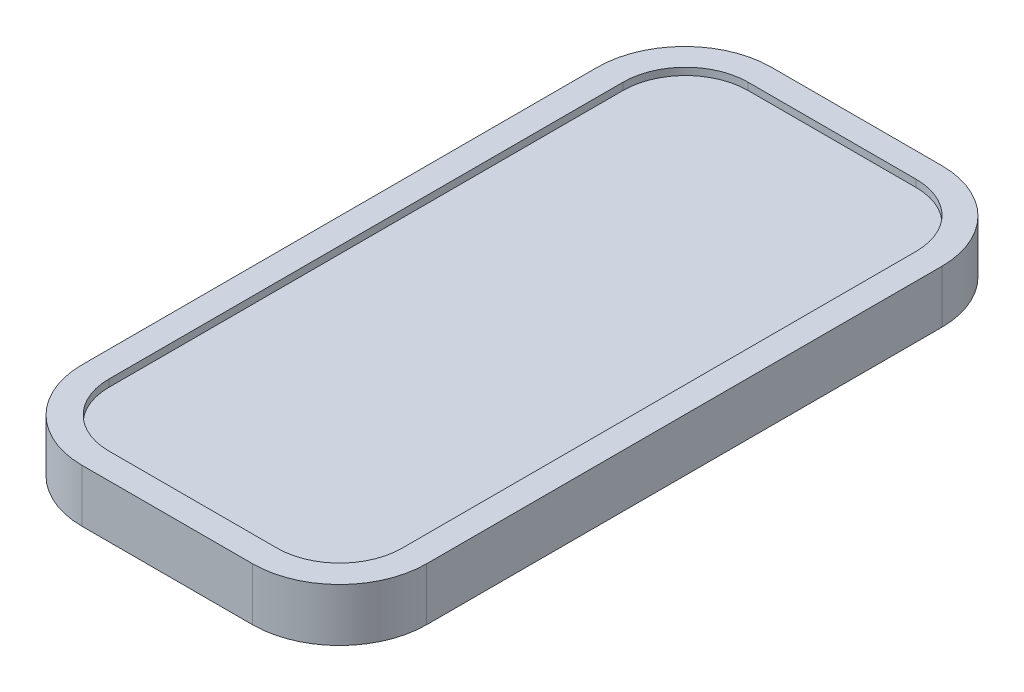
SolidWorks part; units mm, degrees
ref_plane "Front Plane" through (0, 0, 0) normal (0, 0, 1) x (1, 0, 0)
ref_plane "Top Plane" through (0, 0, 0) normal (0, 1, 0) x (1, 0, 0)
ref_plane "Right Plane" through (0, 0, 0) normal (1, 0, 0) x (0, 0, -1)
sketch "Sketch1" plane through (0, 0, 0) normal (0, 1, 0) x (1, 0, 0)
  line L1 (165.1, 0) -> (609.6, 0)
  line L2 (0, 165.1) -> (0, 1524)
  line L3 (165.1, 1689.1) -> (609.6, 1689.1)
  line L4 (774.7, 165.1) -> (774.7, 1524)
  arc A0 (0, 1524) -> (165.1, 1689.1) centre (165.1, 1524) cw
  arc A1 (774.7, 1524) -> (609.6, 1689.1) centre (609.6, 1524) ccw
  arc A2 (0, 165.1) -> (165.1, 0) centre (165.1, 165.1) ccw
  arc A3 (774.7, 165.1) -> (609.6, 0) centre (609.6, 165.1) cw
  point P7 (0, 1689.1)
  point P12 (0, 0)
  point P15 (774.7, 0)
  dimension "D3" = 165.1
  dimension "D4" = 165.1
  dimension "D5" = 165.1
  dimension "D6" = 165.1
  dimension "D1" = 774.7
  dimension "D2" = 1689.1
extrude "Boss-Extrude2" add sketch "Sketch1" against normal blind 10
sketch "Sketch2" plane through (0, 0, 0) normal (0, 1, 0) x (1, 0, 0)
  line L1 (165.1, 0) -> (609.6, 0)
  line L2 (0, 165.1) -> (0, 1524)
  line L3 (165.1, 1689.1) -> (609.6, 1689.1)
  line L4 (774.7, 165.1) -> (774.7, 1524)
  line L5 (162.1025, -68.0875) -> (612.5975, -68.0875)
  line L6 (-68.0875, 162.1025) -> (-68.0875, 1523.9975)
  line L7 (162.1025, 1754.1875) -> (612.5975, 1754.1875)
  line L8 (842.7875, 162.1025) -> (842.7875, 1523.9975)
  arc A0 (165.1, 1689.1) -> (0, 1524) centre (165.1, 1524) ccw
  arc A1 (609.6, 1689.1) -> (774.7, 1524) centre (609.6, 1524) cw
  arc A2 (774.7, 165.1) -> (609.6, 0) centre (609.6, 165.1) cw
  arc A3 (0, 165.1) -> (165.1, 0) centre (165.1, 165.1) ccw
  arc A4 (-68.0875, 162.1025) -> (162.1025, -68.0875) centre (162.1025, 162.1025) ccw
  arc A5 (842.7875, 162.1025) -> (612.5975, -68.0875) centre (612.5975, 162.1025) cw
  arc A6 (612.5975, 1754.1875) -> (842.7875, 1523.9975) centre (612.5975, 1523.9975) cw
  arc A7 (-68.0875, 1523.9975) -> (162.1025, 1754.1875) centre (162.1025, 1523.9975) cw
  point P14 (774.7, 1689.1)
  point P19 (0, 0)
  dimension "D5" = 165.1
  dimension "D6" = 165.1
  dimension "D7" = 165.1
  dimension "D8" = 165.1
  dimension "D9" = 230.19
  dimension "D10" = 230.19
  dimension "D11" = 230.19
  dimension "D12" = 230.19
  dimension "D1" = 65.0875
  dimension "D2" = 68.0875
  dimension "D3" = 68.0875
  dimension "D4" = 68.0875
extrude "Boss-Extrude3" add sketch "Sketch2" along normal blind 19.05 separate body
sketch "Sketch3" plane through (0, 0, 0) normal (0, -1, 0) x (1, 0, 0)
  line L0 (-68.0875, -1523.9975) -> (-68.0875, -162.1025) construction
  line L1 (162.1025, -1754.1875) -> (612.5975, -1754.1875)
  line L2 (-68.0875, -1523.9975) -> (-68.0875, -162.1025)
  line L3 (162.1025, 68.0875) -> (612.5975, 68.0875)
  line L4 (842.7875, -1523.9975) -> (842.7875, -162.1025)
  line L5 (612.5975, -1754.1875) -> (162.1025, -1754.1875) construction
  line L6 (842.7875, -162.1025) -> (842.7875, -1523.9975) construction
  line L7 (162.1025, 68.0875) -> (612.5975, 68.0875) construction
  line L8 (162.1025, -1734.1875) -> (612.5975, -1734.1875)
  line L9 (822.7875, -1523.9975) -> (822.7875, -162.1025)
  line L10 (162.1025, 48.0875) -> (612.5975, 48.0875)
  line L11 (-48.0875, -1523.9975) -> (-48.0875, -162.1025)
  arc A0 (-68.0875, -162.1025) -> (162.1025, 68.0875) centre (162.1025, -162.1025) cw
  arc A1 (842.7875, -162.1025) -> (612.5975, 68.0875) centre (612.5975, -162.1025) ccw
  arc A2 (612.5975, -1754.1875) -> (842.7875, -1523.9975) centre (612.5975, -1523.9975) ccw
  arc A3 (-68.0875, -1523.9975) -> (162.1025, -1754.1875) centre (162.1025, -1523.9975) ccw
  arc A4 (-48.0875, -1523.9975) -> (162.1025, -1734.1875) centre (162.1025, -1523.9975) ccw
  arc A5 (612.5975, -1734.1875) -> (822.7875, -1523.9975) centre (612.5975, -1523.9975) ccw
  arc A6 (822.7875, -162.1025) -> (612.5975, 48.0875) centre (612.5975, -162.1025) ccw
  arc A7 (-48.0875, -162.1025) -> (162.1025, 48.0875) centre (162.1025, -162.1025) cw
  dimension "D5" = 230.19
  dimension "D6" = 230.19
  dimension "D7" = 230.19
  dimension "D8" = 230.19
  dimension "D1" = 0
  dimension "D2" = 0
  dimension "D3" = 0
  dimension "D4" = 0
  dimension "D9" = 20
extrude "Boss-Extrude4" add sketch "Sketch3" along normal blind 120.65
sketch "Sketch4" plane through (0, 0, 0) normal (0, -1, 0) x (1, 0, 0)
  line L0 (612.5975, 48.0875) -> (162.1025, 48.0875) construction
  line L1 (241.3025, 48.0875) -> (533.4025, 48.0875)
  line L2 (241.3025, 48.0875) -> (241.3025, -2.7125)
  line L3 (241.3025, -2.7125) -> (533.4025, -2.7125)
  line L4 (533.4025, 48.0875) -> (533.4025, -2.7125)
  line L5 (-68.0875, -162.1025) -> (-68.0875, -1523.9975) construction
  line L8 (822.7875, -1523.9975) -> (822.7875, -162.1025) construction
  line L9 (822.7875, -256.7125) -> (-48.0875, -256.7125)
  line L10 (822.7875, -256.7125) -> (822.7875, -275.7625)
  line L11 (733.8875, -275.7625) -> (40.8125, -275.7625)
  line L12 (-48.0875, -256.7125) -> (-48.0875, -275.7625)
  line L13 (-48.0875, -162.1025) -> (-48.0875, -1523.9975) construction
  line L14 (822.7875, -224.9625) -> (558.8025, 48.0875)
  line L15 (612.5975, 48.0875) -> (162.1025, 48.0875) construction
  line L16 (215.9025, 48.0875) -> (-48.0875, -224.9625)
  line L17 (-48.0875, -162.1025) -> (-48.0875, -1523.9975) construction
  line L18 (198.2374, 48.0875) -> (-48.0875, -206.6912)
  line L20 (822.7875, -275.7625) -> (822.7875, -364.6625)
  line L21 (822.7875, -364.6625) -> (733.8875, -364.6625)
  line L22 (733.8875, -275.7625) -> (733.8875, -364.6625)
  line L24 (-48.0875, -275.7625) -> (-48.0875, -364.6625)
  line L25 (-48.0875, -364.6625) -> (40.8125, -364.6625)
  line L26 (40.8125, -275.7625) -> (40.8125, -364.6625)
  line L27 (822.7875, -206.691) -> (576.4674, 48.0875)
  line L28 (-48.0875, -224.9625) -> (-48.0875, -206.6912)
  line L29 (206.772, 56.915) -> (-57.218, -216.135) construction
  line L30 (215.9025, 48.0875) -> (198.2374, 48.0875)
  line L31 (822.7875, -224.9625) -> (822.7875, -206.691)
  line L32 (831.918, -216.1351) -> (567.933, 56.9149) construction
  line L33 (558.8025, 48.0875) -> (576.4674, 48.0875)
  dimension "D1" = 292.1
  dimension "D2" = 50.8
  dimension "D3" = 309.39
  dimension "D4" = 19.05
  dimension "D5" = 304.8
  dimension "D6" = 25.4
  dimension "D7" = 31.75
  dimension "D8" = 25.4
  dimension "D9" = 31.75
  dimension "D10" = 88.9
  dimension "D11" = 88.9
  dimension "D12" = 88.9
  dimension "D13" = 88.9
  dimension "D14" = 12.7
extrude "Boss-Extrude7" add sketch "Sketch4" along normal up to surface (115.65 mm away) from offset 5 separate body up to face at (387.35, -120.65, -843.05)
